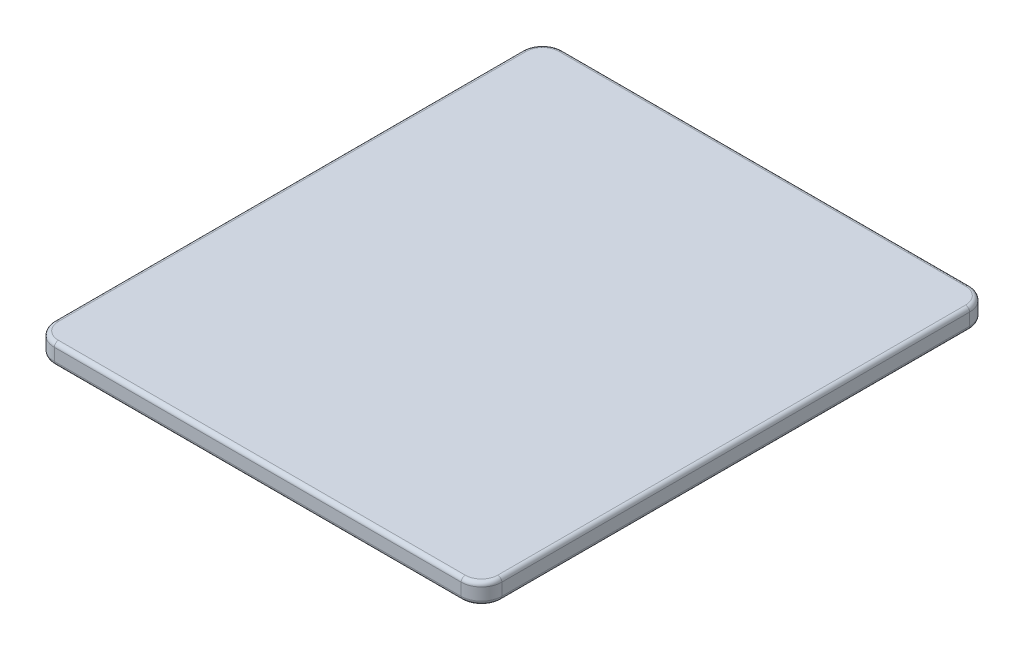
SolidWorks part; units mm, degrees
ref_plane "Front Plane" through (0, 0, 0) normal (0, 0, 1) x (1, 0, 0)
ref_plane "Top Plane" through (0, 0, 0) normal (0, 1, 0) x (1, 0, 0)
ref_plane "Right Plane" through (0, 0, 0) normal (1, 0, 0) x (0, 0, -1)
sketch "Sketch1" plane through (0, 0, 0) normal (0, 1, 0) x (1, 0, 0)
  line L0 (0, 0) -> (0, 19.9304) construction
  line L1 (-5.5, 6.25) -> (5.5, 6.25)
  line L2 (-5.5, 6.25) -> (-5.5, -6.25)
  line L3 (-5.5, -6.25) -> (5.5, -6.25)
  line L4 (5.5, 6.25) -> (5.5, -6.25)
  line L5 (0, 0) -> (18.5687, 0) construction
  dimension "D1" = 12.5
  dimension "D2" = 11
extrude "Boss-Extrude1" add sketch "Sketch1" along normal blind 0.5
fillet "Fillet1" radius 0.5 4 edges at (-5.5, 0.25, -6.25) (5.5, 0.25, -6.25) (-5.5, 0.25, 6.25) (5.5, 0.25, 6.25)
fillet "Fillet2" radius 0.1 16 edges at (-5.3536, 0.5, 6.1036) (-5.5, 0.5, 0) (-5.3536, 0.5, -6.1036) (0, 0.5, -6.25) (5.3536, 0.5, -6.1036) (5.5, 0.5, 0) (5.3536, 0.5, 6.1036) (-5.3536, 0, 6.1036) (0, 0, 6.25) (5.3536, 0, 6.1036) (5.5, 0, 0) (5.3536, 0, -6.1036) (0, 0, -6.25) (-5.3536, 0, -6.1036) (-5.5, 0, 0) (0, 0.5, 6.25)
